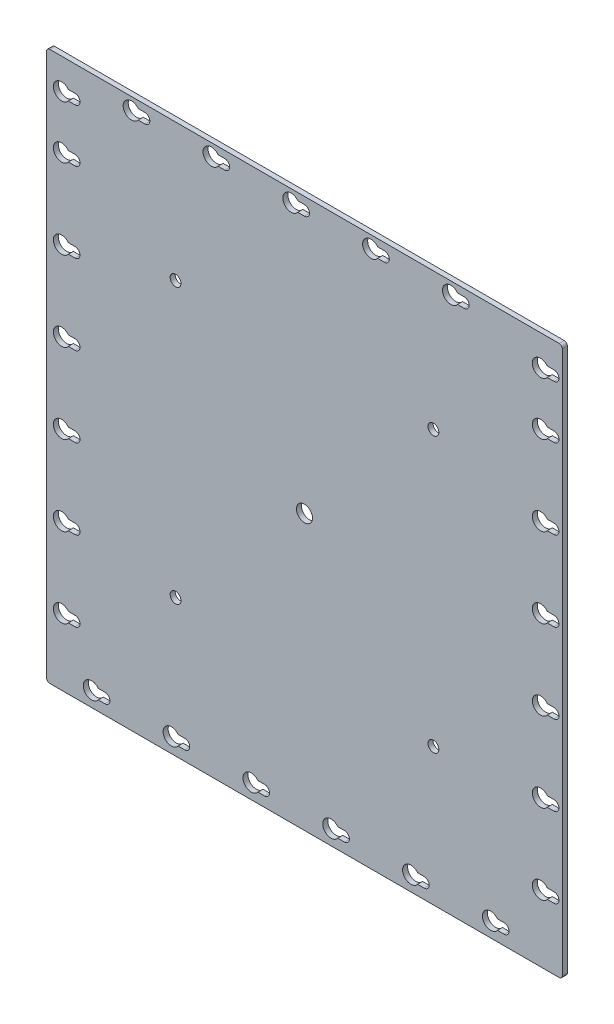
SolidWorks part; units mm, degrees
material "6061 Alloy"
ref_plane "Front Plane" through (0, 0, 0) normal (0, 0, 1) x (1, 0, 0)
ref_plane "Top Plane" through (0, 0, 0) normal (0, 1, 0) x (1, 0, 0)
ref_plane "Right Plane" through (0, 0, 0) normal (1, 0, 0) x (0, 0, -1)
sketch "Sketch1" plane through (0, 0, 0) normal (0, 0, 1) x (1, 0, 0)
  line L0 (0, 0) -> (0, -174.745)
  line L3 (0, -174.745) -> (165.1, -174.745)
  line L5 (0, 0) -> (165.1, 0)
  line L6 (165.1, -174.745) -> (165.1, 0)
  line L7 (82.55, 0) -> (82.55, -174.745) construction
  line L8 (31.75, -2.2625) -> (29.6344, -2.2625)
  line L9 (31.75, -5.4375) -> (29.6344, -5.4375)
  line L10 (9.525, -24.9325) -> (7.4094, -24.9325)
  line L11 (9.525, -28.1075) -> (7.4094, -28.1075)
  line L12 (161.925, -24.9325) -> (159.8094, -24.9325)
  line L13 (161.925, -28.1075) -> (159.8094, -28.1075)
  line L14 (57.15, -2.2625) -> (55.0344, -2.2625)
  line L15 (57.15, -5.4375) -> (55.0344, -5.4375)
  line L16 (82.55, -2.2625) -> (80.4344, -2.2625)
  line L17 (82.55, -5.4375) -> (80.4344, -5.4375)
  line L18 (107.95, -2.2625) -> (105.8344, -2.2625)
  line L19 (107.95, -5.4375) -> (105.8344, -5.4375)
  line L20 (133.35, -2.2625) -> (131.2344, -2.2625)
  line L21 (133.35, -5.4375) -> (131.2344, -5.4375)
  line L22 (9.525, -50.3325) -> (7.4094, -50.3325)
  line L23 (9.525, -53.5075) -> (7.4094, -53.5075)
  line L24 (161.925, -50.3325) -> (159.8094, -50.3325)
  line L25 (161.925, -53.5075) -> (159.8094, -53.5075)
  line L26 (9.525, -75.7325) -> (7.4094, -75.7325)
  line L27 (9.525, -78.9075) -> (7.4094, -78.9075)
  line L28 (161.925, -75.7325) -> (159.8094, -75.7325)
  line L29 (161.925, -78.9075) -> (159.8094, -78.9075)
  line L30 (9.525, -101.1325) -> (7.4094, -101.1325)
  line L31 (9.525, -104.3075) -> (7.4094, -104.3075)
  line L32 (161.925, -101.1325) -> (159.8094, -101.1325)
  line L33 (161.925, -104.3075) -> (159.8094, -104.3075)
  line L34 (9.525, -126.5325) -> (7.4094, -126.5325)
  line L35 (9.525, -129.7075) -> (7.4094, -129.7075)
  line L36 (161.925, -126.5325) -> (159.8094, -126.5325)
  line L37 (161.925, -129.7075) -> (159.8094, -129.7075)
  line L38 (9.525, -151.9325) -> (7.4094, -151.9325)
  line L39 (9.525, -155.1075) -> (7.4094, -155.1075)
  line L40 (161.925, -151.9325) -> (159.8094, -151.9325)
  line L41 (161.925, -155.1075) -> (159.8094, -155.1075)
  line L42 (19.05, -168.395) -> (16.9344, -168.395)
  line L43 (19.05, -171.57) -> (16.9344, -171.57)
  line L44 (44.45, -168.395) -> (42.3344, -168.395)
  line L45 (44.45, -171.57) -> (42.3344, -171.57)
  line L46 (69.85, -168.395) -> (67.7344, -168.395)
  line L47 (69.85, -171.57) -> (67.7344, -171.57)
  line L48 (95.25, -168.395) -> (93.1344, -168.395)
  line L49 (95.25, -171.57) -> (93.1344, -171.57)
  line L50 (120.65, -168.395) -> (118.5344, -168.395)
  line L51 (120.65, -171.57) -> (118.5344, -171.57)
  line L52 (146.05, -168.395) -> (143.9344, -168.395)
  line L53 (146.05, -171.57) -> (143.9344, -171.57)
  line L54 (0.5, 0) -> (0.5, -174.745)
  line L55 (164.6, -174.745) -> (164.6, 0)
  line L56 (0.5, -174.745) -> (164.6, -174.745)
  line L57 (9.525, -8.1) -> (7.4094, -8.1)
  line L58 (9.525, -11.275) -> (7.4094, -11.275)
  line L59 (161.925, -8.1) -> (159.8094, -8.1)
  line L60 (161.925, -11.275) -> (159.8094, -11.275)
  circle A41 centre (9.525, -153.52) radius 1.5875
  circle A42 centre (19.05, -169.9825) radius 1.5875
  circle A43 centre (9.525, -128.12) radius 1.5875
  circle A44 centre (9.525, -102.72) radius 1.5875
  circle A45 centre (9.525, -77.32) radius 1.5875
  circle A46 centre (9.525, -51.92) radius 1.5875
  circle A47 centre (9.525, -26.52) radius 1.5875
  circle A49 centre (44.45, -169.9825) radius 1.5875
  circle A50 centre (69.85, -169.9825) radius 1.5875
  circle A51 centre (95.25, -169.9825) radius 1.5875
  circle A52 centre (120.65, -169.9825) radius 1.5875
  circle A68 centre (146.05, -169.9825) radius 1.5875
  circle A69 centre (107.95, -3.85) radius 1.5875
  circle A70 centre (82.55, -3.85) radius 1.5875
  circle A71 centre (57.15, -3.85) radius 1.5875
  circle A72 centre (9.525, -1.12) radius 1.5875 [skipped]
  circle A73 centre (133.35, -3.85) radius 1.5875
  circle A74 centre (31.75, -3.85) radius 1.5875
  circle A75 centre (161.925, -26.52) radius 1.5875
  circle A76 centre (161.925, -51.92) radius 1.5875
  circle A77 centre (161.925, -77.32) radius 1.5875
  circle A78 centre (161.925, -102.72) radius 1.5875
  circle A79 centre (161.925, -128.12) radius 1.5875
  circle A80 centre (161.925, -153.52) radius 1.5875
  circle A81 centre (27.5125, -3.85) radius 2.65
  circle A83 centre (5.2875, -26.52) radius 2.65
  circle A84 centre (157.6875, -26.52) radius 2.65
  circle A85 centre (52.9125, -3.85) radius 2.65
  circle A86 centre (78.3125, -3.85) radius 2.65
  circle A87 centre (103.7125, -3.85) radius 2.65
  circle A88 centre (129.1125, -3.85) radius 2.65
  circle A89 centre (5.2875, -51.92) radius 2.65
  circle A90 centre (157.6875, -51.92) radius 2.65
  circle A91 centre (5.2875, -77.32) radius 2.65
  circle A92 centre (157.6875, -77.32) radius 2.65
  circle A93 centre (5.2875, -102.72) radius 2.65
  circle A94 centre (157.6875, -102.72) radius 2.65
  circle A95 centre (5.2875, -128.12) radius 2.65
  circle A96 centre (157.6875, -128.12) radius 2.65
  circle A97 centre (5.2875, -153.52) radius 2.65
  circle A98 centre (157.6875, -153.52) radius 2.65
  circle A99 centre (14.8125, -169.9825) radius 2.65
  circle A100 centre (40.2125, -169.9825) radius 2.65
  circle A101 centre (65.6125, -169.9825) radius 2.65
  circle A102 centre (91.0125, -169.9825) radius 2.65
  circle A103 centre (116.4125, -169.9825) radius 2.65
  circle A104 centre (141.8125, -169.9825) radius 2.65
  circle A105 centre (82.55, -87.3725) radius 2.5527
  circle A107 centre (9.525, -9.6875) radius 1.5875
  circle A108 centre (5.2875, -9.6875) radius 2.65
  circle A109 centre (161.925, -9.6875) radius 1.5875
  circle A110 centre (157.6875, -9.6875) radius 2.65
  dimension "D3" = 3.175
  dimension "D8" = 3.175
  dimension "D21" = 5.3
  dimension "D31" = 5.1054
  dimension "D33" = 5.3
  dimension "D1" = 165.1
  dimension "D2" = 174.745
  dimension "D5" = 9.525
  dimension "D4" = 21.225
  dimension "D6" = 19.05
  dimension "D7" = 4.7625
  dimension "D9" = 25.4
  dimension "D10" = 25.4
  dimension "D15" = 25.4
  dimension "D12" = 3.85
  dimension "D13" = 31.75
  dimension "D17" = 31.75
  dimension "D18" = 3.175
  dimension "D20" = 25.4
  dimension "D23" = 25.4
  dimension "D25" = 25.4
  dimension "D27" = 25.4
  dimension "D28" = 0.5
  dimension "D29" = 0.5
  dimension "D30" = 87.3725
  dimension "D34" = 16.8325
  dimension "D35" = 5.8375
  dimension "D11" = 7
  dimension "D14" = 5
  dimension "D16" = 5
  dimension "D19" = 6
  dimension "D22" = 5
  dimension "D24" = 6
  dimension "D26" = 6
extrude "Boss-Extrude1" add sketch "Sketch1" along normal blind 1.6 contours L7 L5 L0 L3 A50 A41 A42 A43 A44 A45 A46 A47 A73 A49 | L5 L7 A70 A105 L56 L55 A84 L12 A75 L13 A87 L18 A69 L19 A88 L20 A73 L21 A90 L24 A76 L25 A92 L28 A77 L29 A94 L32 A78 L33 A96 L36 A79 L37 A98 L40 A80 L41 A102 L48
fillet "Fillet1" radius 1 4 edges at (164.6, 0, 0.8) (164.6, -174.745, 0.8) (0.5, -174.745, 0.8) (0.5, 0, 0.8)
sketch "Sketch2" plane through (0, 0, 1.6) normal (0, 0, 1) x (1, 0, 0)
  line L0 (1.5, 0) -> (163.6, 0) construction
  line L1 (41.525, -43.6863) -> (123.575, -43.6863) construction
  line L2 (41.525, -43.6863) -> (41.525, -131.0588) construction
  line L3 (41.525, -131.0588) -> (123.575, -131.0588) construction
  line L4 (123.575, -43.6863) -> (123.575, -131.0588) construction
  line L5 (41.525, -43.6863) -> (123.575, -131.0588) construction
  line L6 (41.525, -131.0588) -> (123.575, -43.6863) construction
  line L8 (164.6, -1) -> (0.5, -1) construction
  line L9 (0.5, -1) -> (0.5, -173.745) construction
  line L10 (164.6, -173.745) -> (164.6, -1) construction
  line L11 (1.5, 0) -> (1.5, -174.745) construction
  circle A0 centre (41.525, -43.6863) radius 1.725
  circle A1 centre (123.575, -43.6863) radius 1.725
  circle A2 centre (123.575, -131.0588) radius 1.725
  circle A3 centre (41.525, -131.0588) radius 1.725
  point P4 (82.55, -87.3725)
  point P11 (82.55, 0)
  point P25 (55.2, -131.5515)
  dimension "D7" = 3.45
  dimension "D1" = 164.1
  dimension "D2" = 41.025
  dimension "D3" = 41.025
  dimension "D5" = 174.745
  dimension "D6" = 43.6863
  dimension "D4" = 43.6863
extrude "Cut-Extrude1" cut sketch "Sketch2" against normal through all both
equation "\"D8@Sketch1\"=\"D3@Sketch1\""
equation "\"D29@Sketch1\"=\"D28@Sketch1\""
equation "\"D30@Sketch1\"=\"D2@Sketch1\"/2"
equation "\"D2@Sketch2\"=\"D1@Sketch2\"/4"
equation "\"D6@Sketch2\"=\"D5@Sketch2\"/4"
equation "\"D4@Sketch2\"=\"D5@Sketch2\"/4"
